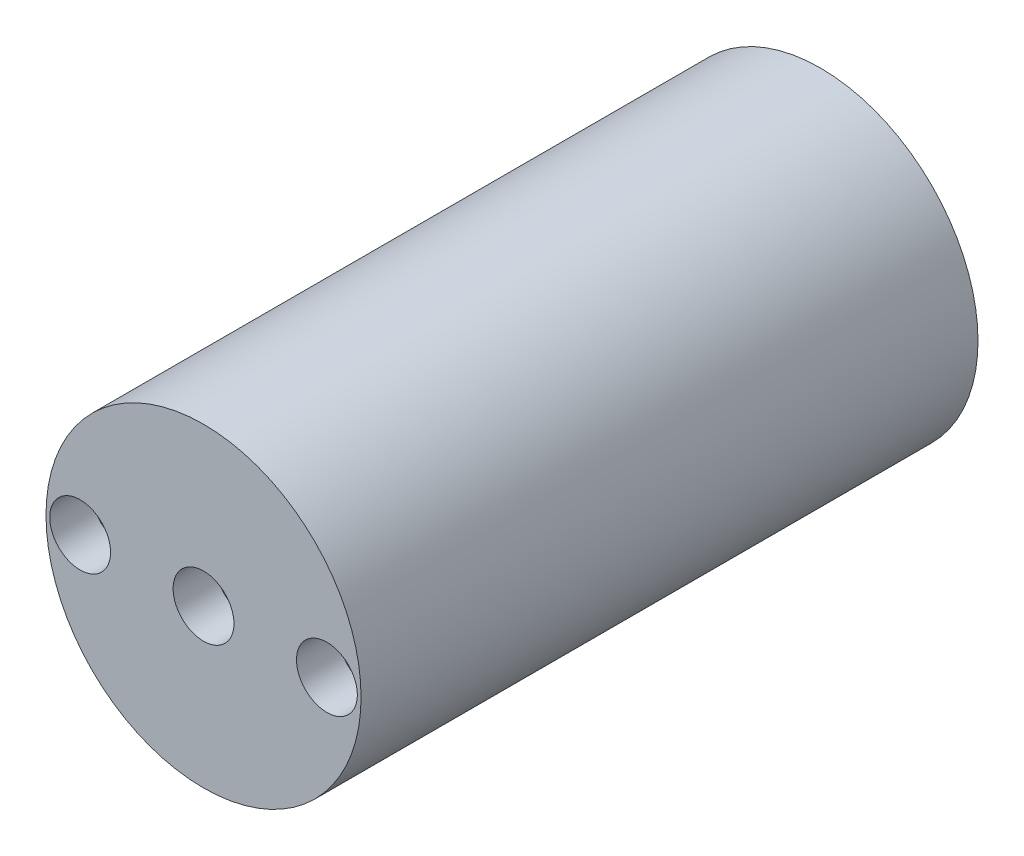
SolidWorks part; units mm, degrees
ref_plane "Front Plane" through (0, 0, 0) normal (0, 0, 1) x (1, 0, 0)
ref_plane "Top Plane" through (0, 0, 0) normal (0, 1, 0) x (1, 0, 0)
ref_plane "Right Plane" through (0, 0, 0) normal (1, 0, 0) x (0, 0, -1)
sketch "Sketch6" plane through (0, 0, 0) normal (0, 0, 1) x (1, 0, 0)
  circle A0 centre (0, 0) radius 19.15
  dimension "D1" = 38.3
extrude "Boss-Extrude3" add sketch "Sketch6" along normal blind 75
sketch "Sketch9" plane through (0, 0, 75) normal (0, 0, 1) x (1, 0, 0)
  line L0 (-19.15, 0) -> (19.15, 0) construction
  circle A0 centre (0, 0) radius 19.15 construction
  circle A1 centre (0, 0) radius 3.7
  circle A2 centre (-15, 0) radius 3.7
  circle A3 centre (15, 0) radius 3.7
  dimension "D1" = 7.4
  dimension "D2" = 7.4
  dimension "D3" = 7.4
  dimension "D4" = 15
  dimension "D5" = 15
extrude "Cut-Extrude2" cut sketch "Sketch9" against normal blind 5.15
